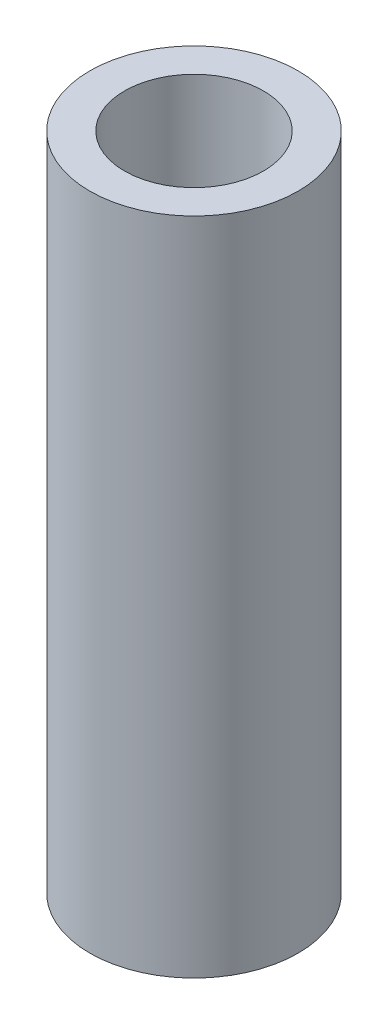
SolidWorks part; units mm, degrees
ref_plane "Front Plane" through (0, 0, 0) normal (0, 0, 1) x (1, 0, 0)
ref_plane "Top Plane" through (0, 0, 0) normal (0, 1, 0) x (1, 0, 0)
ref_plane "Right Plane" through (0, 0, 0) normal (1, 0, 0) x (0, 0, -1)
sketch "Sketch2" plane through (0, 0, 0) normal (0, 1, 0) x (1, 0, 0)
  circle A0 centre (0, 0) radius 30
  circle A1 centre (0, 0) radius 20
  dimension "D1" = 60
  dimension "D2" = 40
extrude "Boss-Extrude1" add sketch "Sketch2" along normal blind 190 contours A1 | A0
